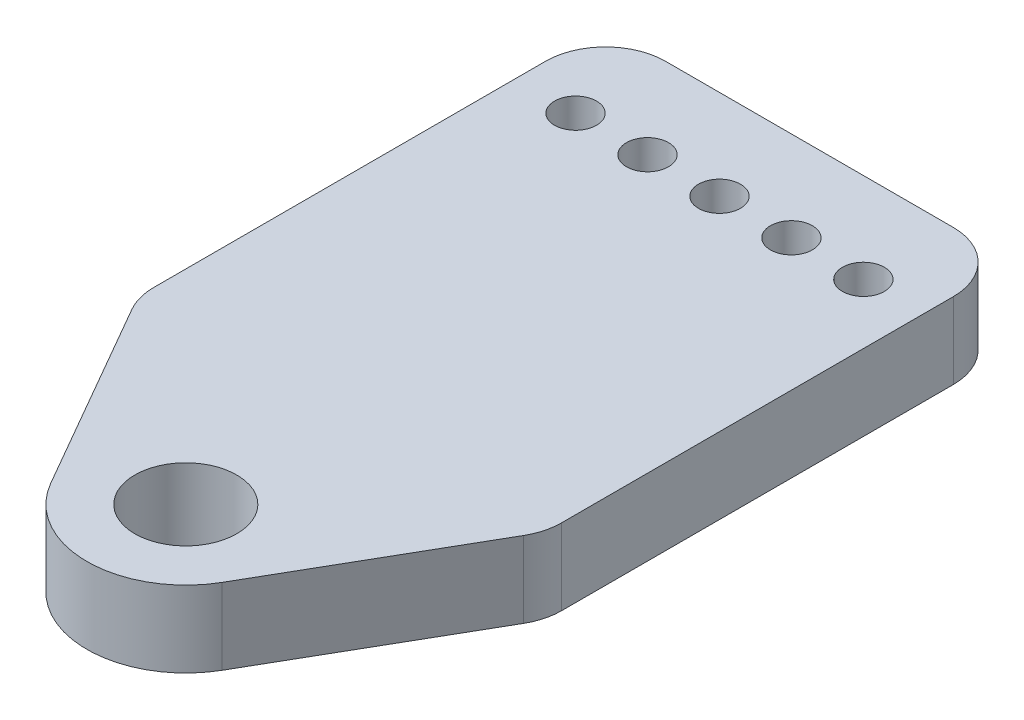
SolidWorks part; units mm, degrees
ref_plane "Front Plane" through (0, 0, 0) normal (0, 0, 1) x (1, 0, 0)
ref_plane "Top Plane" through (0, 0, 0) normal (0, 1, 0) x (1, 0, 0)
ref_plane "Right Plane" through (0, 0, 0) normal (1, 0, 0) x (0, 0, -1)
sketch "Sketch1" plane through (0, 0, 0) normal (0, 1, 0) x (1, 0, 0)
  line L0 (12, 0) -> (12, -44.5) construction
  line L1 (12, 0) -> (12, 7.5) construction
  line L2 (-5, 7.5) -> (29, 7.5)
  line L3 (29, 7.5) -> (29, -31.5)
  line L4 (-5, 7.5) -> (-5, -31.5)
  line L5 (-5, -31.5) -> (4.8495, -48.615)
  line L6 (29, -31.5) -> (19.1505, -48.615)
  circle A0 centre (0, 0) radius 1.75
  circle A1 centre (6, 0) radius 1.75
  circle A2 centre (12, 0) radius 1.75
  circle A3 centre (18, 0) radius 1.75
  circle A4 centre (24, 0) radius 1.75
  circle A5 centre (12, -44.5) radius 4.25
  arc A6 (4.8495, -48.615) -> (19.1505, -48.615) centre (12, -44.5) ccw
  circle A7 centre (12, -44.5) radius 8.25 construction
  point P17 (12, 7.5)
  dimension "D1" = 3.5
  dimension "D4" = 8.5
  dimension "D5" = 7.5
  dimension "D6" = 5
  dimension "D3" = 52
  dimension "D8" = 39
  dimension "D7" = 4
  dimension "D2" = 5
extrude "Boss-Extrude1" add sketch "Sketch1" along normal blind 6.35
fillet "Fillet1" radius 5 4 edges at (-5, 3.175, -7.5) (-5, 3.175, 31.5) (29, 3.175, 31.5) (29, 3.175, -7.5)
equation "\"M3_Hole\"= 3.5mm'Loose fit for M3 screw"
equation "\"M8_Hole\"= 8.5mm'Loose fit for M8 screw"
equation "\"D1@Sketch1\"=\"M3_Hole\""
equation "\"D4@Sketch1\"=\"M8_Hole\""
equation "\"Wheel_Diameter\"= 100mm'Nexus Mecanum wheel"
equation "\"Extrusion_Width\"= 15mm'15mm Misumi extrusion"
equation "\"Wheel_Gap\"= 2mm'Gap from top extrusion to wheel"
equation "\"Wheel offset\"= ( \"Wheel_Diameter\" / 2 ) + \"Wheel_Gap\"'Wheel axel offset from top of chassis"
equation "\"D3@Sketch1\"=\"Wheel offset\""
equation "\"D8@Sketch1\"=\"Wheel offset\" * 0.75"
